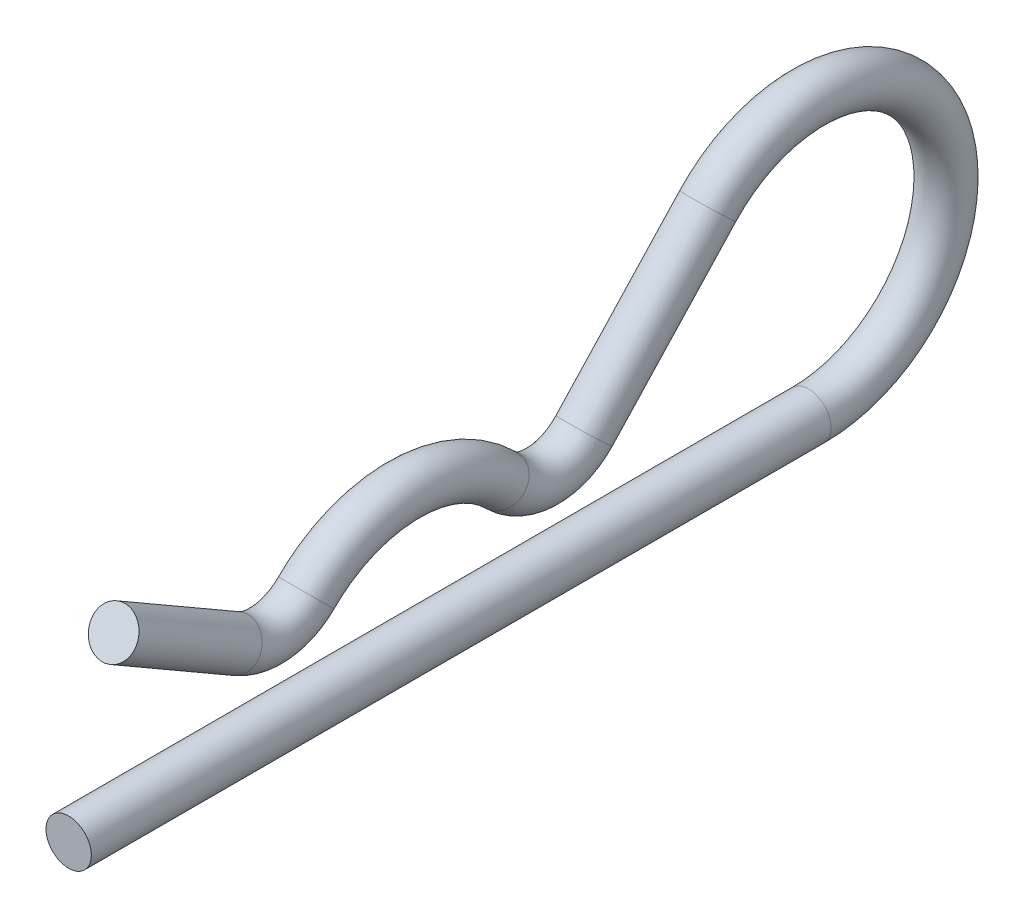
SolidWorks part; units mm, degrees
ref_plane "Front" through (0, 0, 0) normal (0, 0, 1) x (1, 0, 0)
ref_plane "Top" through (0, 0, 0) normal (0, 1, 0) x (1, 0, 0)
ref_plane "Right" through (0, 0, 0) normal (1, 0, 0) x (0, 0, -1)
sketch "Sketch1" plane through (0, 0, 0) normal (1, 0, 0) x (0, 0, -1)
  line L0 (-37.3062, -11.4046) -> (24.0221, -11.4046) construction
  line L1 (-20.9841, 0) -> (1.9341, 0) construction
  line L2 (37.3062, -11.4046) -> (37.3062, 0) construction
  line L3 (37.3062, 0) -> (35.4267, 0) construction
  line L4 (-37.3062, -11.4046) -> (-37.3062, -9.525) construction
  line L5 (37.3062, -11.4046) -> (-37.3062, -11.4046) construction
  line L6 (-23.3653, -4.1244) -> (-33.5756, 1.7705) construction
  line L7 (-9.525, 0) -> (-9.525, -11.4046) construction
  line L8 (-37.3062, -11.4046) -> (-37.3062, -13.2842) construction
  line L9 (37.3062, -11.4046) -> (37.3062, 11.4046) construction
  line L10 (37.3062, 11.4046) -> (-37.3062, 11.4046) construction
  line L11 (-37.3062, 11.4046) -> (-37.3062, -11.4046) construction
  line L12 (0, 11.4046) -> (0, -11.4046) construction
  line L13 (15.6746, 7.7707) -> (5.4199, -3.245) construction
  circle A0 centre (24.0221, 0) radius 9.525 construction
  arc A1 (-1.4415, -3.3596) -> (-17.6085, -3.3596) centre (-9.525, -11.4046) ccw construction
  arc A6 (-17.6085, -3.3596) -> (-23.3653, -4.1244) centre (-20.9841, 0) cw construction
  arc A8 (5.4199, -3.245) -> (-1.4415, -3.3596) centre (1.9341, 0) cw construction
  arc A9 (24.0221, -11.4046) -> (15.6746, 7.7707) centre (24.0221, 0) ccw construction
  point P2 (0, 0)
  dimension "D1" = 4.7625
  dimension "Eye Diameter" = 19.05
  dimension "D2" = 27.7812
  dimension "D5" = 3.7306
  dimension "D9" = 30
  dimension "D11" = 1.8796
  dimension "D3" = 1.8796
  dimension "Length" = 74.6125
  dimension "Wire Diameter" = 3.7592
ref_plane "Plane1" through (0, 0, 37.3062) normal (0, 0, 1) x (1, 0, 0)
sketch "Sketch2" plane through (0, 0, 37.3062) normal (0, 0, 1) x (1, 0, 0)
  circle A0 centre (0, -11.4046) radius 1.8796
sketch "Sketch3" plane through (0, 0, 0) normal (1, 0, 0) x (0, 0, -1)
  line L0 (-23.3653, -4.1244) -> (-33.5756, 1.7705) construction
  line L1 (15.6746, 7.7707) -> (5.4199, -3.245) construction
  line L2 (-37.3062, -11.4046) -> (24.0221, -11.4046) construction
  line L3 (-23.3653, -4.1244) -> (-33.5756, 1.7705)
  line L4 (15.6746, 7.7707) -> (5.4199, -3.245)
  line L5 (-37.3062, -11.4046) -> (24.0221, -11.4046)
  arc A0 (-23.3653, -4.1244) -> (-17.6085, -3.3596) centre (-20.9841, 0) ccw construction
  arc A1 (-1.4415, -3.3596) -> (-17.6085, -3.3596) centre (-9.525, -11.4046) ccw construction
  arc A2 (-1.4415, -3.3596) -> (5.4199, -3.245) centre (1.9341, 0) ccw construction
  arc A3 (24.0221, -11.4046) -> (15.6746, 7.7707) centre (24.0221, 0) ccw construction
  arc A4 (-23.3653, -4.1244) -> (-17.6085, -3.3596) centre (-20.9841, 0) ccw
  arc A5 (-1.4415, -3.3596) -> (-17.6085, -3.3596) centre (-9.525, -11.4046) ccw
  arc A6 (-1.4415, -3.3596) -> (5.4199, -3.245) centre (1.9341, 0) ccw
  arc A7 (24.0221, -11.4046) -> (15.6746, 7.7707) centre (24.0221, 0) ccw
sweep "Sweep1" add profiles "Sketch2" path "Sketch3"
equation "\"D11@Sketch1\" = \"Wire Diameter@Sketch1\" / 2"
equation "\"D1@Sketch1\" = \"Eye Diameter@Sketch1\" / 4"
equation "\"D3@Sketch1\" = \"D11@Sketch1\""
equation "\"D2@Sketch1\" =  ( \"Length@Sketch1\" - \"Eye Diameter@Sketch1\" )  / 2"
equation "\"D5@Sketch1\" = \"Length@Sketch1\" * .05"
